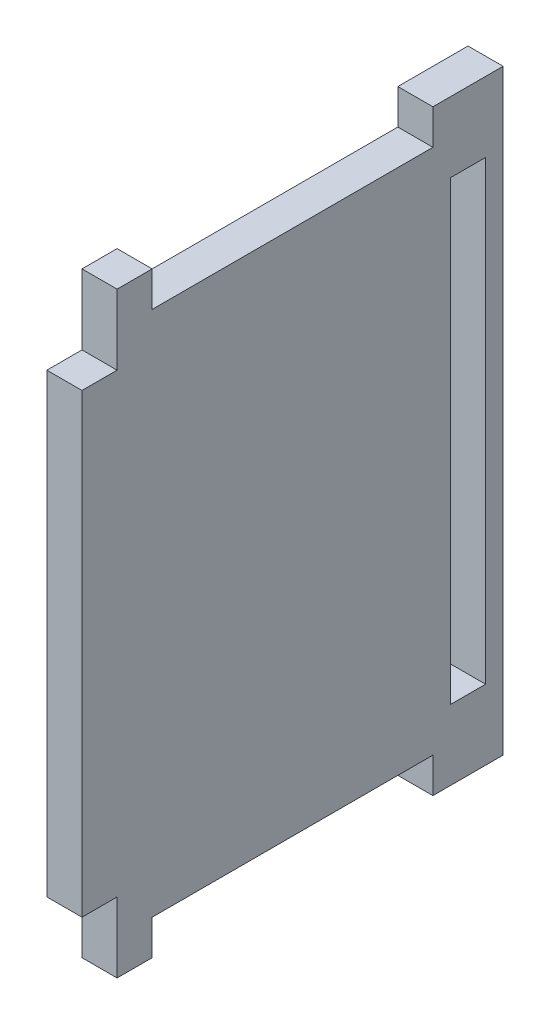
SolidWorks part; units mm, degrees
ref_plane "Front Plane" through (0, 0, 0) normal (0, 0, 1) x (1, 0, 0)
ref_plane "Top Plane" through (0, 0, 0) normal (0, 1, 0) x (1, 0, 0)
ref_plane "Right Plane" through (0, 0, 0) normal (1, 0, 0) x (0, 0, -1)
sketch "Sketch1" plane through (0, 0, 0) normal (0, 0, 1) x (1, 0, 0)
  line L0 (-114.3, 101.6) -> (82.55, 101.6) construction
  line L1 (82.55, -6.35) -> (76.2, -6.35)
  line L2 (82.55, -6.35) -> (82.55, 101.6)
  line L3 (82.55, 101.6) -> (76.2, 101.6)
  line L4 (76.2, -6.35) -> (76.2, 101.6)
  dimension "D1" = 6.35
extrude "Boss-Extrude1" add sketch "Sketch1" along normal up to surface (76.2 mm away)
sketch "Sketch2" plane through (82.55, 0, 0) normal (1, 0, 0) x (0, 0, -1)
  line L0 (-69.85, -6.35) -> (-69.85, 6.35) construction
  line L1 (-76.2, 101.6) -> (-69.85, 101.6)
  line L2 (-76.2, 101.6) -> (-76.2, 88.9)
  line L3 (-76.2, 88.9) -> (-69.85, 88.9)
  line L4 (-69.85, 101.6) -> (-69.85, 88.9)
  line L6 (-76.2, -6.35) -> (-69.85, -6.35)
  line L7 (-76.2, -6.35) -> (-76.2, 6.35)
  line L8 (-76.2, 6.35) -> (-69.85, 6.35)
  line L9 (-69.85, -6.35) -> (-69.85, 6.35)
  line L13 (-12.7, 95.25) -> (-12.7, 101.6)
  line L14 (-12.7, 101.6) -> (-63.5, 101.6)
  line L15 (-63.5, 101.6) -> (-63.5, 95.25)
  line L16 (-63.5, 95.25) -> (-12.7, 95.25)
  line L17 (-12.7, 95.25) -> (-12.7, 101.6)
  line L18 (-12.7, 101.6) -> (-63.5, 101.6)
  line L19 (-63.5, 101.6) -> (-63.5, 95.25)
  line L20 (-63.5, 95.25) -> (-12.7, 95.25)
  line L21 (-3.175, 6.35) -> (-3.175, 88.9)
  line L22 (-3.175, 88.9) -> (-9.525, 88.9)
  line L23 (-9.525, 88.9) -> (-9.525, 6.35)
  line L24 (-9.525, 6.35) -> (-3.175, 6.35)
  line L25 (-3.175, 6.35) -> (-3.175, 88.9)
  line L26 (-3.175, 88.9) -> (-9.525, 88.9)
  line L27 (-9.525, 88.9) -> (-9.525, 6.35)
  line L28 (-9.525, 6.35) -> (-3.175, 6.35)
  line L29 (-12.7, 0) -> (-63.5, 0)
  line L30 (-63.5, 0) -> (-63.5, -6.35)
  line L31 (-63.5, -6.35) -> (-12.7, -6.35)
  line L32 (-12.7, -6.35) -> (-12.7, 0)
  line L33 (-12.7, 0) -> (-63.5, 0)
  line L34 (-63.5, 0) -> (-63.5, -6.35)
  line L35 (-63.5, -6.35) -> (-12.7, -6.35)
  line L36 (-12.7, -6.35) -> (-12.7, 0)
  dimension "D1" = 12.7
  dimension "D2" = 0
  dimension "D3" = 0
  dimension "D4" = 0
extrude "Cut-Extrude1" cut sketch "Sketch2" against normal through all
